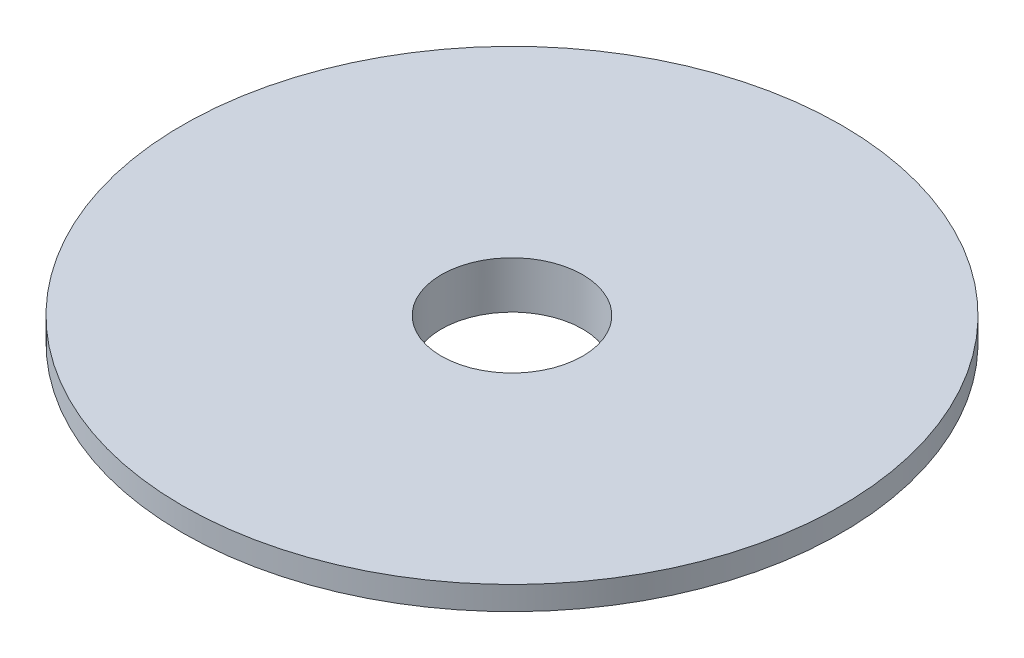
SolidWorks part; units mm, degrees
ref_plane "Front Plane" through (0, 0, 0) normal (0, 0, 1) x (1, 0, 0)
ref_plane "Top Plane" through (0, 0, 0) normal (0, 1, 0) x (1, 0, 0)
ref_plane "Right Plane" through (0, 0, 0) normal (1, 0, 0) x (0, 0, -1)
sketch "Sketch1" plane through (0, 0, 0) normal (0, 1, 0) x (1, 0, 0)
  circle A0 centre (0, 0) radius 88.9
  circle A1 centre (0, 0) radius 19.05
  dimension "D1" = 38.1
  dimension "D2" = 177.8
extrude "Boss-Extrude1" add sketch "Sketch1" along normal blind 6.35
sketch "Sketch3" plane through (0, 0, 0) normal (0, -1, 0) x (1, 0, 0)
  circle A0 centre (0, 0) radius 19.05
  circle A1 centre (0, 0) radius 25.4
  dimension "D1" = 38.1
  dimension "D2" = 50.8
extrude "Boss-Extrude3" add sketch "Sketch3" along normal blind 6.35
